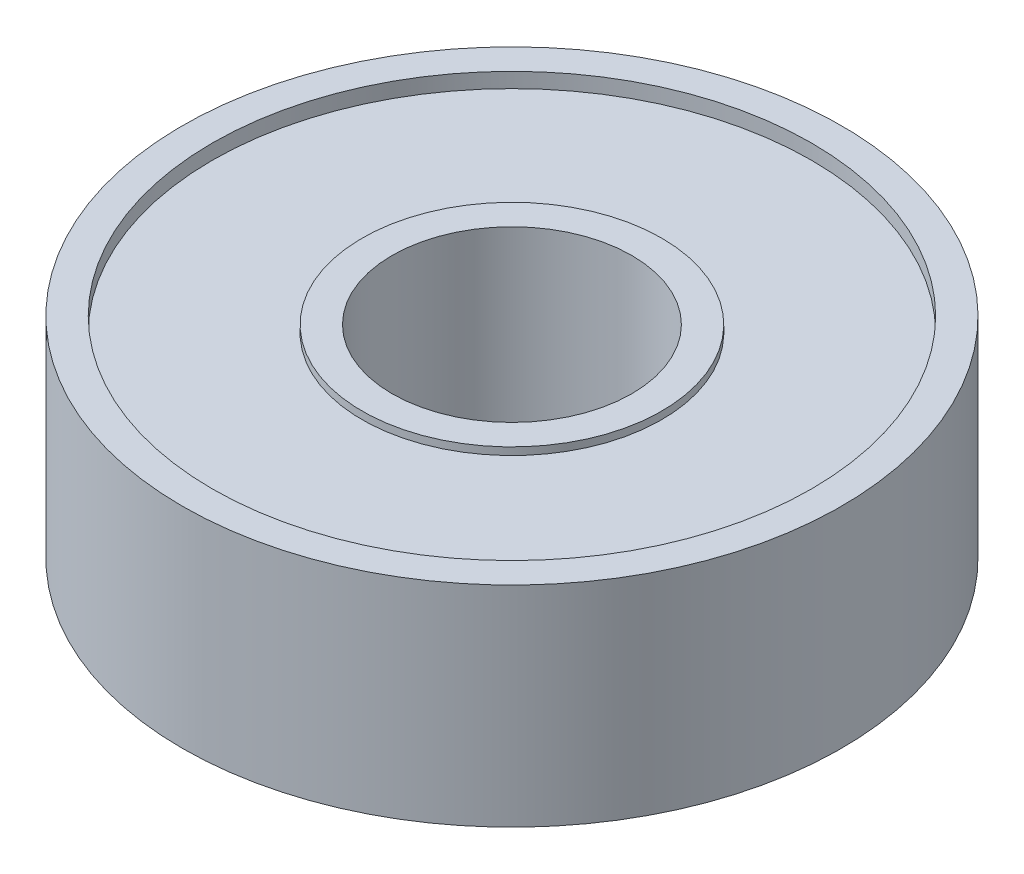
SolidWorks part; units mm, degrees
ref_plane "Front Plane" through (0, 0, 0) normal (0, 0, 1) x (1, 0, 0)
ref_plane "Top Plane" through (0, 0, 0) normal (0, 1, 0) x (1, 0, 0)
ref_plane "Right Plane" through (0, 0, 0) normal (1, 0, 0) x (0, 0, -1)
sketch "Sketch1" plane through (0, 0, 0) normal (0, 1, 0) x (1, 0, 0)
  circle A0 centre (0, 0) radius 11
  dimension "D1" = 22
extrude "Boss-Extrude1" add sketch "Sketch1" along normal mid plane 6
sketch "Sketch2" plane through (0, 0, 0) normal (0, 1, 0) x (1, 0, 0)
  circle A1 centre (0, 0) radius 11
  circle A2 centre (0, 0) radius 10
  dimension "D2" = 1
extrude "Boss-Extrude2" add sketch "Sketch2" along normal mid plane 7
sketch "Sketch4" plane through (0, 0, 0) normal (0, 1, 0) x (1, 0, 0)
  circle A0 centre (0, 0) radius 27.5915
  circle A2 centre (0, 0) radius 5
  dimension "D1" = 10
extrude "Boss-Extrude3" add sketch "Sketch4" along normal mid plane 6.5 contours A2
sketch "Sketch5" plane through (0, 3.25, 0) normal (0, 1, 0) x (1, 0, 0)
  circle A0 centre (0, 0) radius 4
  circle A2 centre (0, 0) radius 5 construction
  dimension "D1" = 1
extrude "Cut-Extrude1" cut sketch "Sketch5" against normal blind 10
